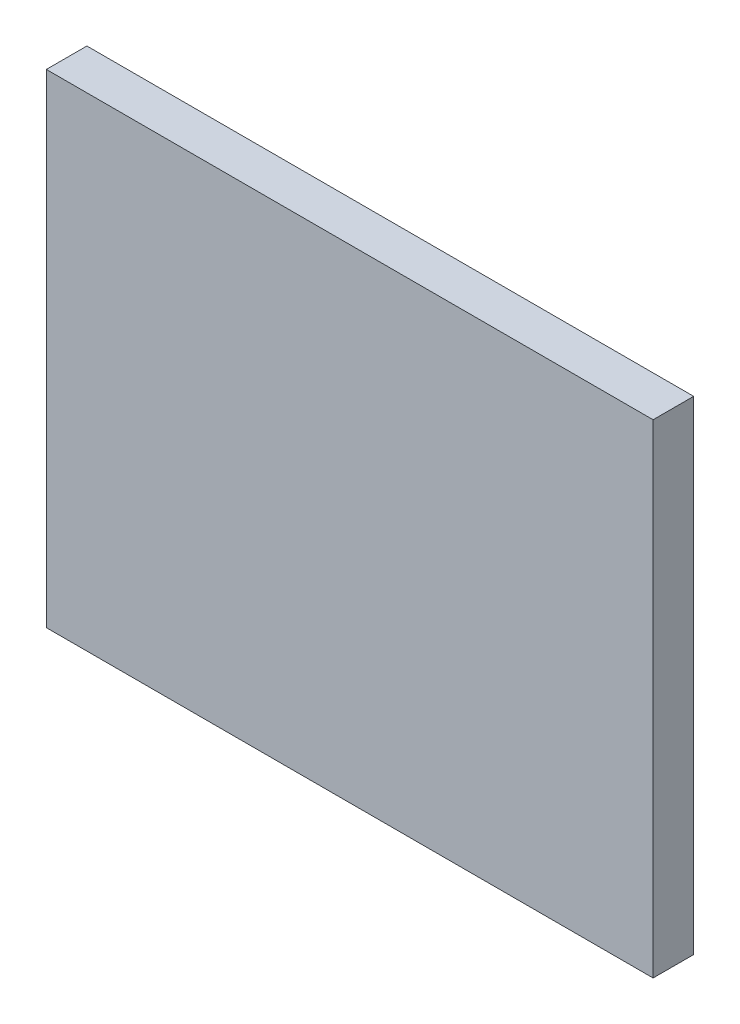
SolidWorks part; units mm, degrees
ref_plane "Front Plane" through (0, 0, 0) normal (0, 0, 1) x (1, 0, 0)
ref_plane "Top Plane" through (0, 0, 0) normal (0, 1, 0) x (1, 0, 0)
ref_plane "Right Plane" through (0, 0, 0) normal (1, 0, 0) x (0, 0, -1)
sketch "Sketch1" plane through (0, 0, 0) normal (0, 0, 1) x (1, 0, 0)
  line L1 (-23.749, 18.923) -> (23.749, 18.923)
  line L2 (-23.749, 18.923) -> (-23.749, -18.923)
  line L3 (-23.749, -18.923) -> (23.749, -18.923)
  line L4 (23.749, 18.923) -> (23.749, -18.923)
  line L5 (-23.749, 18.923) -> (23.749, -18.923) construction
  line L6 (-23.749, -18.923) -> (23.749, 18.923) construction
  point P0 (0, 0)
  dimension "D1" = 47.498
  dimension "D2" = 37.846
extrude "Boss-Extrude1" add sketch "Sketch1" along normal blind 3.175
